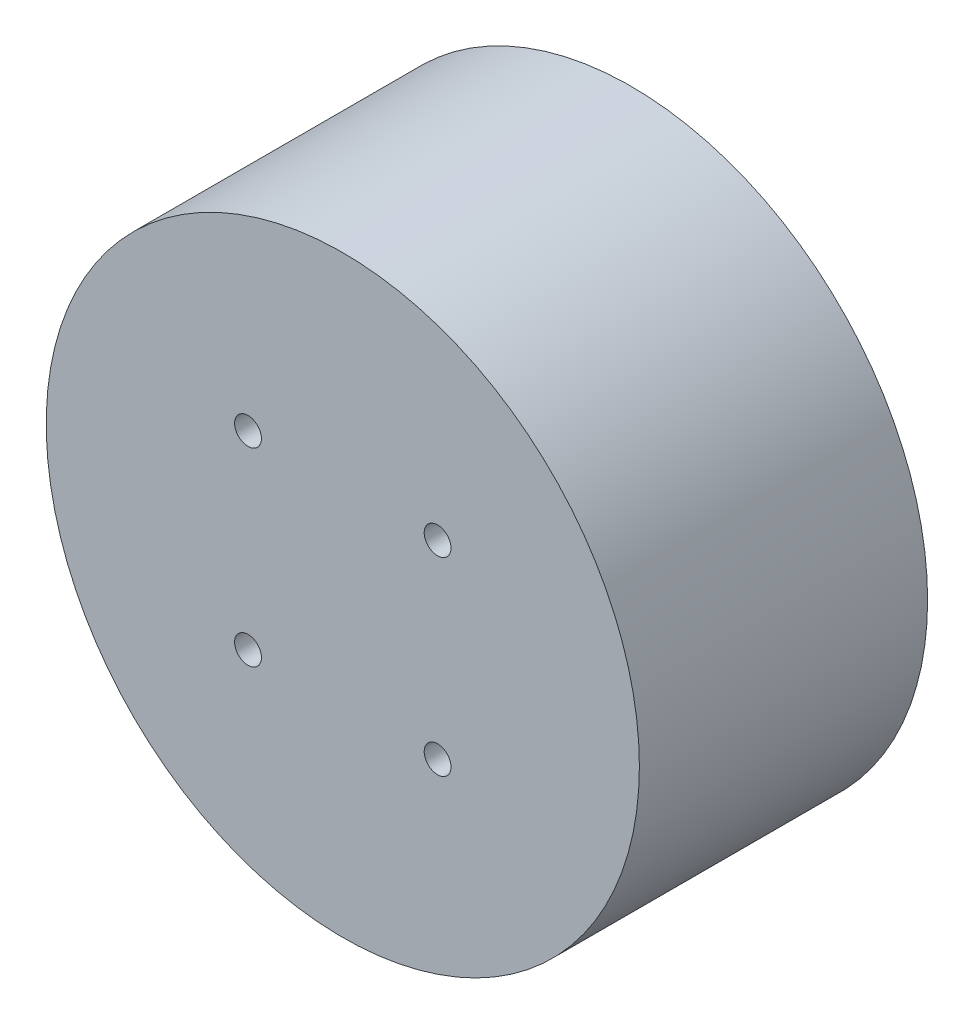
SolidWorks part; units mm, degrees
ref_plane "前视基准面" through (0, 0, 0) normal (0, 0, 1) x (1, 0, 0)
ref_plane "上视基准面" through (0, 0, 0) normal (0, 1, 0) x (1, 0, 0)
ref_plane "右视基准面" through (0, 0, 0) normal (1, 0, 0) x (0, 0, -1)
sketch "草图1" plane through (0, 0, 0) normal (0, 0, 1) x (1, 0, 0)
  circle A0 centre (0, 0) radius 44.25
  dimension "D1" = 88.5
extrude "凸台-拉伸1" add sketch "草图1" along normal blind 43 contours A0
sketch "草图2" plane through (0, 0, 43) normal (0, 0, 1) x (1, 0, 0)
  line L1 (-14.1421, -14.1421) -> (14.1421, -14.1421) construction
  line L2 (-14.1421, -14.1421) -> (-14.1421, 14.1421) construction
  line L3 (-14.1421, 14.1421) -> (14.1421, 14.1421) construction
  line L4 (14.1421, -14.1421) -> (14.1421, 14.1421) construction
  line L5 (-14.1421, -14.1421) -> (14.1421, 14.1421) construction
  line L6 (-14.1421, 14.1421) -> (14.1421, -14.1421) construction
  circle A0 centre (0, 0) radius 20 construction
  circle A1 centre (-14.1421, 14.1421) radius 2
  circle A2 centre (14.1421, 14.1421) radius 2
  circle A3 centre (-14.1421, -14.1421) radius 2
  circle A4 centre (14.1421, -14.1421) radius 2
  dimension "D1" = 40
  dimension "D2" = 4
  dimension "D3" = 4
  dimension "D4" = 4
  dimension "D5" = 4
extrude "切除-拉伸1" cut sketch "草图2" against normal blind 8
sketch "草图3" plane through (0, 0, 0) normal (0, 0, -1) x (-1, 0, 0)
  line L0 (0, -15.5) -> (0, 15.5) construction
  line L1 (-15.5, 0) -> (15.5, 0) construction
  circle A0 centre (0, 0) radius 15.5 construction
  circle A1 centre (0, 15.5) radius 1.5
  circle A2 centre (15.5, 0) radius 1.5
  circle A3 centre (-15.5, 0) radius 1.5
  circle A4 centre (0, -15.5) radius 1.5
  point P6 (0, 0)
  point P9 (0, 0)
  dimension "D1" = 31
  dimension "D2" = 3
  dimension "D3" = 3
  dimension "D4" = 3
  dimension "D5" = 3
extrude "切除-拉伸2" cut sketch "草图3" against normal blind 20
